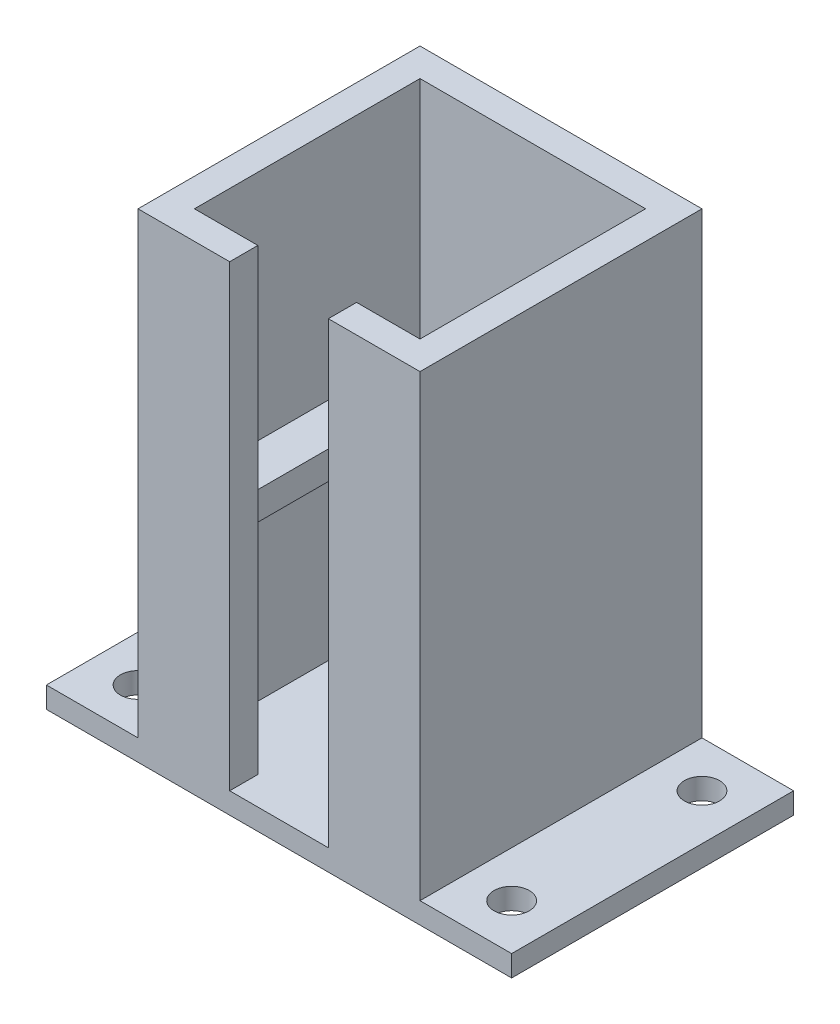
SolidWorks part; units mm, degrees
ref_plane "Front Plane" through (0, 0, 0) normal (0, 0, 1) x (1, 0, 0)
ref_plane "Top Plane" through (0, 0, 0) normal (0, 1, 0) x (1, 0, 0)
ref_plane "Right Plane" through (0, 0, 0) normal (1, 0, 0) x (0, 0, -1)
sketch "Sketch1" plane through (0, 0, 0) normal (0, 1, 0) x (1, 0, 0)
  line L0 (-111.7041, 65.9949) -> (-111.7041, 25.9949)
  line L1 (-111.7041, 25.9949) -> (-45.7041, 25.9949)
  line L2 (-45.7041, 25.9949) -> (-45.7041, 65.9949)
  line L3 (-45.7041, 65.9949) -> (-111.7041, 65.9949)
  line L4 (-111.7041, 65.9949) -> (-98.7041, 65.9949) construction
  circle A0 centre (-105.2041, 59.4949) radius 2.5
  circle A1 centre (-105.2041, 32.4949) radius 2.5
  circle A2 centre (-52.2041, 59.4949) radius 2.5
  circle A3 centre (-52.2041, 32.4949) radius 2.5
extrude "Boss-Extrude1" add sketch "Sketch1" along normal blind 3 contours L3 L0 L1 L2 | A1 | A0 | A2 | A3
sketch "Sketch2" plane through (0, 3, 0) normal (0, 1, 0) x (1, 0, 0)
  line L0 (-111.7041, 65.9949) -> (-98.7041, 65.9949) construction
  line L1 (-45.7041, 65.9949) -> (-111.7041, 65.9949) construction
  line L2 (-98.7041, 65.9949) -> (-58.7041, 65.9949)
  line L3 (-58.7041, 65.9949) -> (-58.7041, 25.9949)
  line L4 (-111.7041, 25.9949) -> (-45.7041, 25.9949) construction
  line L5 (-98.7041, 65.9949) -> (-98.7041, 25.9949)
  line L6 (-94.7041, 61.9949) -> (-62.7041, 61.9949)
  line L8 (-62.7041, 61.9949) -> (-62.7041, 29.9949)
  line L9 (-94.7041, 61.9949) -> (-94.7041, 29.9949)
  line L10 (-94.7041, 29.9949) -> (-85.7041, 29.9949)
  line L11 (-85.7041, 29.9949) -> (-85.7041, 25.9949)
  line L12 (-85.7041, 25.9949) -> (-98.7041, 25.9949)
  line L13 (-62.7041, 29.9949) -> (-71.7041, 29.9949)
  line L14 (-71.7041, 29.9949) -> (-71.7041, 25.9949)
  line L15 (-71.7041, 25.9949) -> (-58.7041, 25.9949)
extrude "Boss-Extrude2" add sketch "Sketch2" along normal blind 65
sketch "Sketch3" plane through (0, 0, -61.9949) normal (0, 0, 1) x (1, 0, 0)
  line L1 (-94.7041, 68) -> (-94.7041, 3) construction
  line L2 (-94.7041, 35) -> (-88.7041, 35)
  line L3 (-88.7041, 35) -> (-88.7041, 31)
  line L4 (-88.7041, 31) -> (-94.7041, 31)
  line L5 (-94.7041, 31) -> (-94.7041, 35)
  line L6 (-62.7041, 35) -> (-68.7041, 35)
  line L7 (-62.7041, 68) -> (-62.7041, 3) construction
  line L8 (-68.7041, 35) -> (-68.7041, 31)
  line L9 (-68.7041, 31) -> (-62.7041, 31)
  line L10 (-62.7041, 31) -> (-62.7041, 35)
extrude "Boss-Extrude3" add sketch "Sketch3" along normal blind 32
